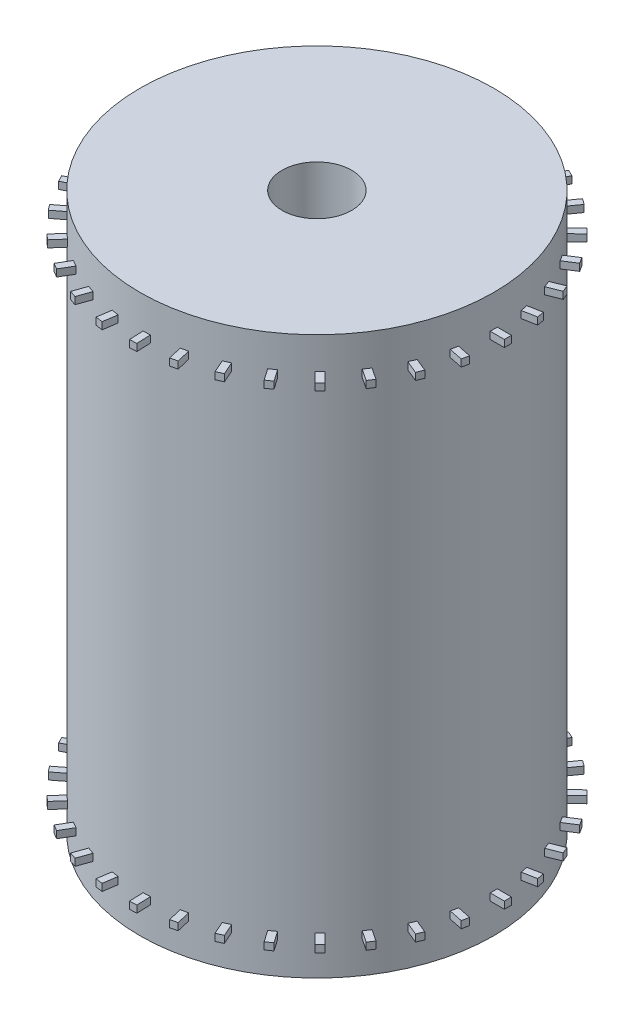
SolidWorks part; units mm, degrees
ref_plane "Front Plane" through (0, 0, 0) normal (0, 0, 1) x (1, 0, 0)
ref_plane "Top Plane" through (0, 0, 0) normal (0, 1, 0) x (1, 0, 0)
ref_plane "Right Plane" through (0, 0, 0) normal (1, 0, 0) x (0, 0, -1)
sketch "Sketch1" plane through (0, 0, 0) normal (0, 1, 0) x (1, 0, 0)
  circle A0 centre (0, 0) radius 12.7
  dimension "D1" = 25.4
extrude "Boss-Extrude1" add sketch "Sketch1" along normal blind 40
hole_wizard "Ø5.0mm Dowel Hole1" positions "Sketch5" profile "Sketch6" hole size "Ø5.0" standard "ANSI Metric" end condition through all
sketch "Sketch5" plane through (0, 40, 0) normal (0, 1, 0) x (1, 0, 0)
  point P0 (0, 0)
sketch "Sketch6" plane through (0, 40, 0) normal (1, 0, 0) x (0, 0, 1)
  line L0 (0, 0) -> (0, 40)
  line L1 (0, 40) -> (2.5, 40)
  line L2 (2.5, 40) -> (2.5, 0)
  line L5 (2.5, 0) -> (0, 0)
  line L11 (0, -6.35) -> (0, 107.95) construction
  dimension "Thru Hole Dia." = 5
  dimension "Thru Hole Depth" = 40
sketch "Sketch4" plane through (0, 40, 0) normal (0, 1, 0) x (1, 0, 0)
  line L1 (12.6975, 0.254) -> (13.7135, 0.254)
  line L2 (12.6975, 0.254) -> (12.6975, -0.254)
  line L3 (12.6975, -0.254) -> (13.7135, -0.254)
  line L4 (13.7135, 0.254) -> (13.7135, -0.254)
  circle A1 centre (0, 0) radius 12.7
  circle A2 centre (0, 0) radius 12.7
  circle M12 centre (0, 0) radius 12.7
  dimension "D2" = 0.508
  dimension "D3" = 1.016
extrude "Boss-Extrude2" add sketch "Sketch4" along normal blind 0.508 from offset 2.794 contours L4 L1 L3 M12 offset against normal yes
ref_plane "Plane1" through (0, 20, 0) normal (0, 1, 0) x (1, 0, 0)
mirror "Mirror4" about plane through (0, 20, 0) normal (0, 1, 0) of "Boss-Extrude2"
pattern_circular "CirPattern3" count 33 every 10.886 about axis through (0, 0, 0) along (0, 1, 0) of "Boss-Extrude2", "Mirror4"
equation "\"diamiter\"= 1"
equation "\"D1@Sketch1\"=\"diamiter\""
equation "\"tooth width\"= 0.5mm"
equation "\"Tooth Depth\"= 1mm"
equation "\"D2@Sketch4\"=\"tooth width\""
equation "\"D3@Sketch4\"=\"Tooth Depth\""
equation "\"Tooth height\"= 0.5mm"
equation "\"tooth offset\"= 2.5mm"
equation "\"D1@Boss-Extrude2\"=\"Tooth height\""
equation "\"D19@Boss-Extrude2\"=\"tooth offset\"+\"Tooth height\"/2"
equation "\"Number of teeth\"= 10"
equation "\"D1@CirPattern1\"=\"Number of teeth\""
equation "\"hole distance\"= 0.187"
equation "\"angle spacing\"= ( \"hole distance\" * 360 ) / ( 2 * pi * \"diamiter\" )"
equation "\"D2@CirPattern3\"=\"angle spacing\""
